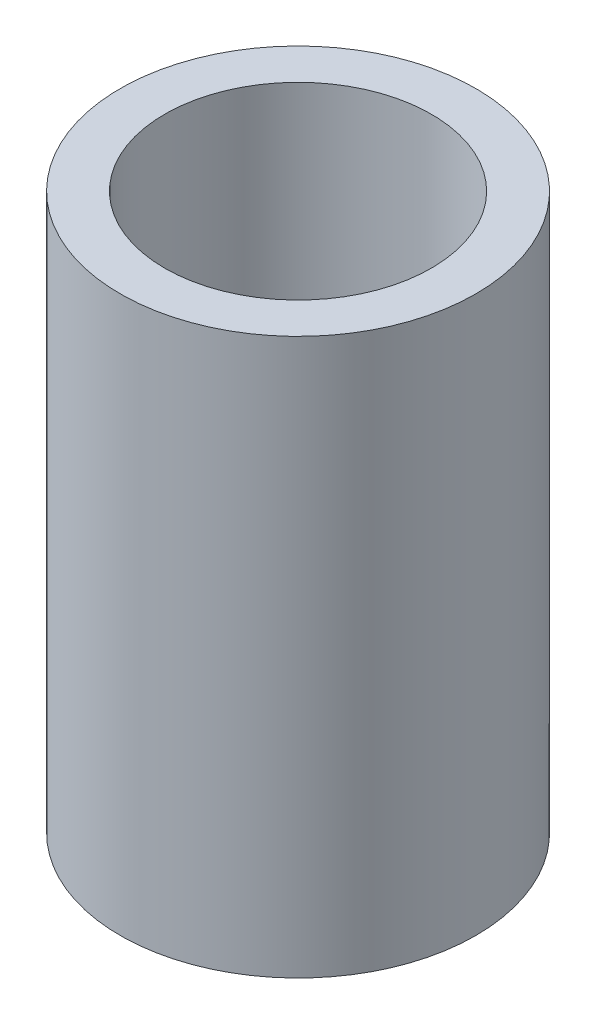
SolidWorks part; units mm, degrees
ref_plane "Front Plane" through (0, 0, 0) normal (0, 0, 1) x (1, 0, 0)
ref_plane "Top Plane" through (0, 0, 0) normal (0, 1, 0) x (1, 0, 0)
ref_plane "Right Plane" through (0, 0, 0) normal (1, 0, 0) x (0, 0, -1)
sketch "Sketch1" plane through (0, 0, 0) normal (0, 1, 0) x (1, 0, 0)
  circle A0 centre (0, 0) radius 6
  dimension "D1" = 12
extrude "Extrude-Thin1" add sketch "Sketch1" along normal blind 25 thin
